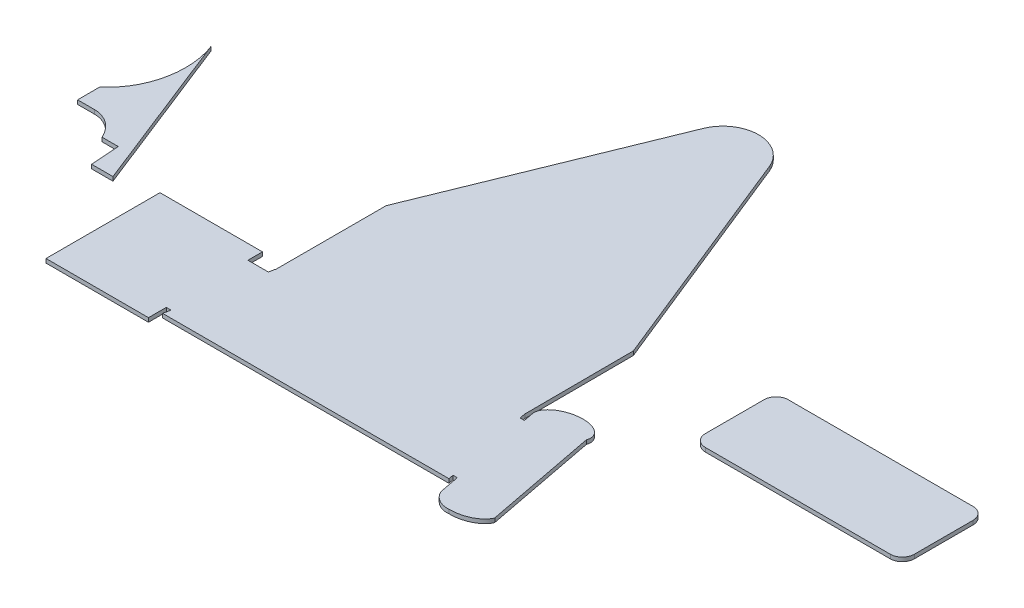
SolidWorks part; units mm, degrees
ref_plane "Front Plane" through (0, 0, 0) normal (0, 0, 1) x (1, 0, 0)
ref_plane "Top Plane" through (0, 0, 0) normal (0, 1, 0) x (1, 0, 0)
ref_plane "Right Plane" through (0, 0, 0) normal (1, 0, 0) x (0, 0, -1)
sketch "Sketch1" plane through (0, 0, 0) normal (0, 1, 0) x (1, 0, 0)
  line L0 (52.713, -200.4636) -> (47.7903, -129.1547)
  line L1 (47.7903, -129.1547) -> (7.5466, -129.1547)
  line L2 (-103.6291, -22.9229) -> (-103.4622, -79.0492)
  line L3 (-103.4622, -79.0492) -> (-61.7833, -79.0492)
  line L4 (-52.8709, 202.3058) -> (105.8398, -200.4636)
  line L5 (105.8398, -200.4636) -> (52.713, -200.4636)
  ellipse E0 centre (-178.4622, 124.9791) end of major axis (-178.4622, 299.9791) minor radius 140 (-103.6291, -22.9229) -> (-52.8709, 202.3058) ccw
  spline S0 degree 3 poles (-61.7833, -79.0492) (-59.6246, -79.112) (-55.4279, -79.2343) (-49.3891, -80.1723) (-43.8528, -81.5135) (-38.8743, -83.1721) (-34.4868, -84.9976) (-30.7044, -86.8632) (-26.3726, -89.3012) (-21.4959, -92.5283) (-12.95, -99.3437) (-2.2538, -111.0227) (4.5665, -122.6854) (7.5466, -129.1547) knots 0 0 0 0 0.045442 0.088347 0.128406 0.165307 0.198742 0.228422 0.254087 0.303421 0.351448 0.484303 0.635079 0.635079 0.635079 0.635079
extrude "Boss-Extrude1" add sketch "Sketch1" along normal blind 10 contours L4 L5 L0 L1 S0 L3 L2 E0
sketch "Sketch3" plane through (0, 0, 0) normal (0, 1, 0) x (1, 0, 0)
  line L0 (1128.8997, 71.5182) -> (899.9973, 639.8052)
  line L1 (737.3139, 639.8238) -> (508.4031, 76.7272)
  line L2 (508.4031, 76.7272) -> (508.4031, -199.4834)
  line L3 (508.4031, -199.4834) -> (507.4031, -199.8556)
  line L4 (507.4031, -199.8556) -> (504.9046, -212.8455)
  line L5 (504.9046, -212.8455) -> (454.0521, -212.8455)
  line L6 (454.0521, -212.8455) -> (454.0521, -176.6757)
  line L7 (454.0521, -176.6757) -> (199.0521, -176.6757)
  line L8 (199.0521, -176.6757) -> (199.0521, -460.2987)
  line L9 (199.0521, -460.2987) -> (454.0521, -460.2987)
  line L10 (454.0521, -460.2987) -> (454.0521, -415.9922)
  line L11 (454.0521, -415.9922) -> (465.8307, -415.9922)
  line L12 (465.8307, -415.9922) -> (462.4693, -433.4684)
  line L13 (462.4693, -433.4684) -> (818.6514, -433.4684)
  line L14 (818.6514, -433.4684) -> (1174.8335, -433.4684)
  line L15 (1174.8335, -433.4684) -> (1172.4286, -420.9649)
  line L16 (1172.4286, -420.9649) -> (1183.0945, -420.9649)
  line L17 (1183.0945, -420.9649) -> (1192.8584, -471.7286)
  line L18 (1316.3967, -461.0118) -> (1262.1434, -178.9447)
  line L19 (1138.6051, -189.6615) -> (1143.3228, -214.189)
  line L20 (1143.3228, -214.189) -> (1132.6139, -213.9655)
  line L21 (1132.6139, -213.9655) -> (1129.8997, -199.8542)
  line L22 (1129.8997, -199.8542) -> (1128.8997, 71.5182)
  arc A0 (899.9973, 639.8052) -> (737.3139, 639.8238) centre (818.6515, 604.3216) ccw
  arc A1 (1192.8584, -471.7286) -> (1241.1609, -499.1708) centre (1236.4471, -451.237) ccw
  ellipse E0 centre (1255.2155, -459.7347) end of major axis (1192.8584, -471.7286) minor radius 38.2787 (1241.1609, -499.1708) -> (1316.3967, -461.0118) ccw
  ellipse E1 centre (1200.9622, -177.6676) end of major axis (1263.3192, -165.6738) minor radius 38.2787 (1262.1434, -178.9447) -> (1138.6051, -189.6615) ccw
extrude "Boss-Extrude2" add sketch "Sketch3" along normal blind 10 separate body contours L0 A0 L1 L2 L3 L4 L5 L6 L7 L8 L9 L10 L11 L12 L13 L14 L15 L16 L17 A1 E0 L18 E1 L19 L20 L21 L22
sketch "Sketch4" plane through (0, 0, 0) normal (0, 1, 0) x (1, 0, 0)
  line L0 (1426.7085, -47.1987) -> (1886.7085, -47.1987)
  line L1 (1886.7085, 158.8013) -> (1426.7085, 158.8013)
  line L2 (1396.7085, 128.8013) -> (1396.7085, -17.1987)
  line L3 (1916.7085, -17.1987) -> (1916.7085, 128.8013)
  arc A0 (1426.7085, 158.8013) -> (1396.7085, 128.8013) centre (1426.7085, 128.8013) ccw
  arc A1 (1396.7085, -17.1987) -> (1426.7085, -47.1987) centre (1426.7085, -17.1987) ccw
  arc A2 (1886.7085, -47.1987) -> (1916.7085, -17.1987) centre (1886.7085, -17.1987) ccw
  arc A3 (1916.7085, 128.8013) -> (1886.7085, 158.8013) centre (1886.7085, 128.8013) ccw
extrude "Boss-Extrude3" add sketch "Sketch4" along normal blind 10 separate body
